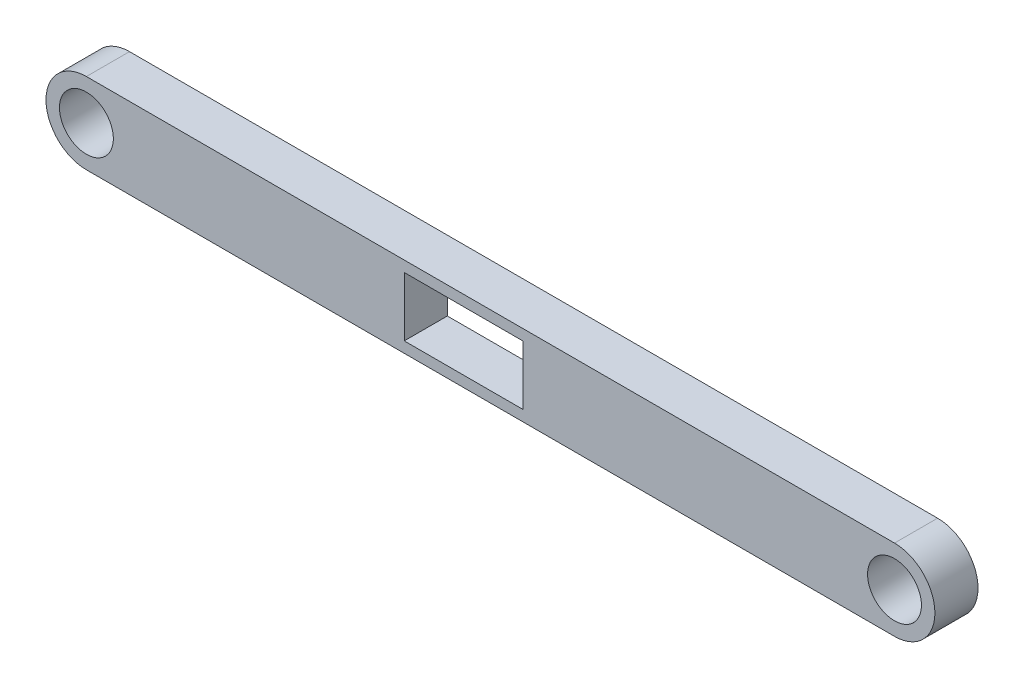
SolidWorks part; units mm, degrees
ref_plane "Front Plane" through (0, 0, 0) normal (0, 0, 1) x (1, 0, 0)
ref_plane "Top Plane" through (0, 0, 0) normal (0, 1, 0) x (1, 0, 0)
ref_plane "Right Plane" through (0, 0, 0) normal (1, 0, 0) x (0, 0, -1)
sketch "Sketch1" plane through (0, 0, 0) normal (0, 0, 1) x (1, 0, 0)
  line L0 (75, 0) -> (-75, 0) construction
  line L1 (75, -7.5) -> (-75, -7.5)
  line L2 (75, 7.5) -> (-75, 7.5)
  line L3 (0, 7.5) -> (0, -7.5) construction
  line L5 (-16, 5.5) -> (6, 5.5)
  line L6 (-16, 5.5) -> (-16, -5.5)
  line L7 (-16, -5.5) -> (6, -5.5)
  line L8 (6, 5.5) -> (6, -5.5)
  line L9 (-16, 5.5) -> (6, -5.5) construction
  line L10 (-16, -5.5) -> (6, 5.5) construction
  arc A0 (75, -7.5) -> (75, 7.5) centre (75, 0) ccw
  arc A1 (-75, 7.5) -> (-75, -7.5) centre (-75, 0) ccw
  circle A2 centre (75, 0) radius 5
  circle A3 centre (-75, 0) radius 5
  point P2 (0, 0)
  point P14 (-5, 0)
  point P19 (0, 0)
  point P21 (0, 0)
  dimension "D2" = 10
  dimension "D1" = 150
  dimension "D3" = 15
  dimension "D4" = 22
  dimension "D5" = 11
  dimension "D6" = 6
extrude "Boss-Extrude1" add sketch "Sketch1" along normal blind 8
